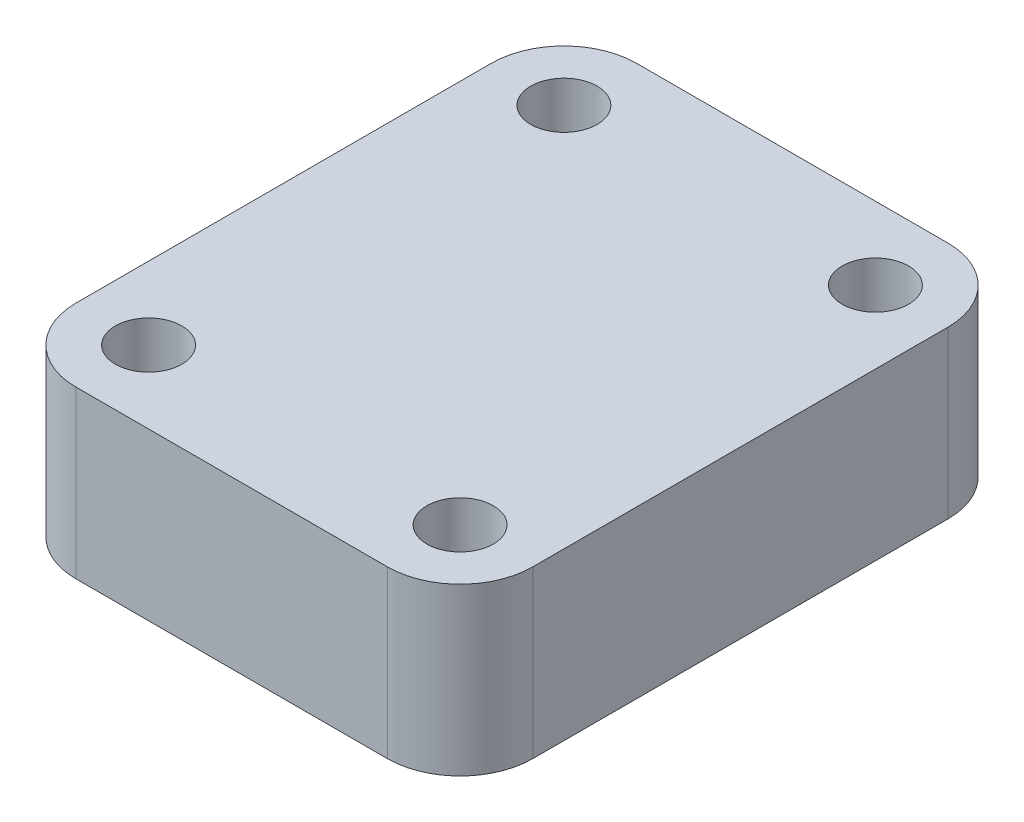
SolidWorks part; units mm, degrees
material "6061-T6 (SS)"
ref_plane "Front Plane" through (0, 0, 0) normal (0, 0, 1) x (1, 0, 0)
ref_plane "Top Plane" through (0, 0, 0) normal (0, 1, 0) x (1, 0, 0)
ref_plane "Right Plane" through (0, 0, 0) normal (1, 0, 0) x (0, 0, -1)
sketch "Sketch1" plane through (0, 0, 0) normal (0, 1, 0) x (1, 0, 0)
  line L1 (7.5, -10) -> (-7.5, -10) construction
  line L2 (7.5, -10) -> (7.5, 10) construction
  line L3 (7.5, 10) -> (-7.5, 10) construction
  line L4 (-7.5, -10) -> (-7.5, 10) construction
  line L5 (7.5, -10) -> (-7.5, 10) construction
  line L6 (7.5, 10) -> (-7.5, -10) construction
  line L7 (11, -13.5) -> (-11, -13.5)
  line L8 (11, -13.5) -> (11, 13.5)
  line L9 (11, 13.5) -> (-11, 13.5)
  line L10 (-11, -13.5) -> (-11, 13.5)
  line L11 (11, -13.5) -> (-11, 13.5) construction
  line L12 (11, 13.5) -> (-11, -13.5) construction
  circle A0 centre (-7.5, 10) radius 1.5 construction
  circle A1 centre (7.5, 10) radius 1.5 construction
  circle A2 centre (7.5, -10) radius 1.5 construction
  circle A3 centre (-7.5, -10) radius 1.5 construction
  point P0 (0, 0)
  point P10 (0, 0)
  dimension "D3" = 3
  dimension "D1" = 20
  dimension "D2" = 15
  dimension "D4" = 3.5
  dimension "D5" = 3.5
extrude "Boss-Extrude1" add sketch "Sketch1" along normal blind 8
hole_wizard "M3 Clearance Hole1" positions "Sketch2" profile "Sketch3" hole size "M3" standard "ANSI Metric" end condition through all
sketch "Sketch2" plane through (0, 8, 0) normal (0, 1, 0) x (1, 0, 0)
  point P0 (-7.5, -10)
  point P3 (-7.5, 10)
  point P6 (7.5, 10)
  point P9 (7.5, -10)
sketch "Sketch3" plane through (-7.5, 8, 10) normal (1, 0, 0) x (0, 0, 1)
  line L0 (0, 0) -> (0, 8)
  line L1 (0, 8) -> (1.6, 8)
  line L2 (1.6, 8) -> (1.6, 0)
  line L5 (1.6, 0) -> (0, 0)
  line L11 (0, -6.35) -> (0, 107.95) construction
  dimension "Thru Hole Dia." = 3.2
  dimension "Thru Hole Depth" = 8
fillet "Fillet1" radius 3.5 4 edges at (-11, 4, -13.5) (11, 4, -13.5) (11, 4, 13.5) (-11, 4, 13.5)
